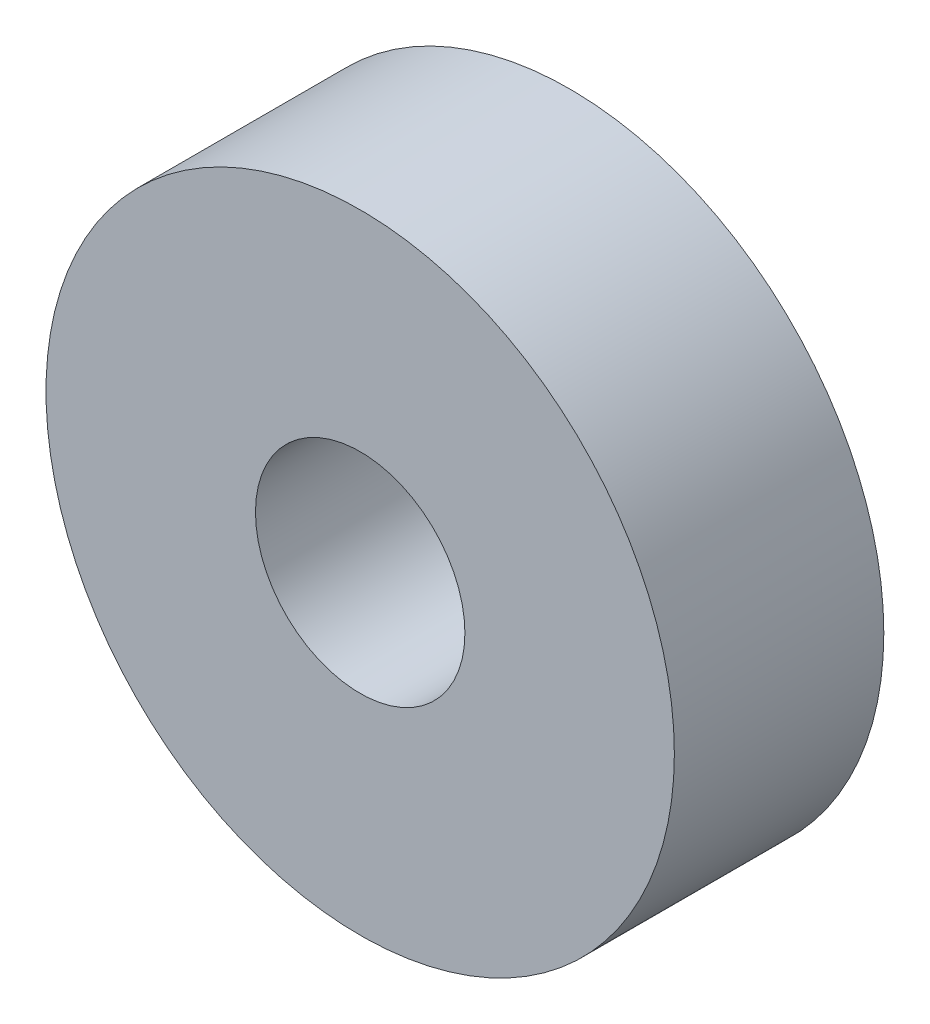
SolidWorks part; units mm, degrees
ref_plane "Alzado" through (0, 0, 0) normal (0, 0, 1) x (1, 0, 0)
ref_plane "Planta" through (0, 0, 0) normal (0, 1, 0) x (1, 0, 0)
ref_plane "Vista lateral" through (0, 0, 0) normal (1, 0, 0) x (0, 0, -1)
sketch "Model" plane through (0, 0, 0) normal (0, 0, 1) x (1, 0, 0)
  circle A0 centre (115.4856, 217.5371) radius 4.5
  circle A1 centre (115.4856, 217.5371) radius 1.5
extrude "Saliente-Extruir1" add sketch "Model" along normal blind 3
